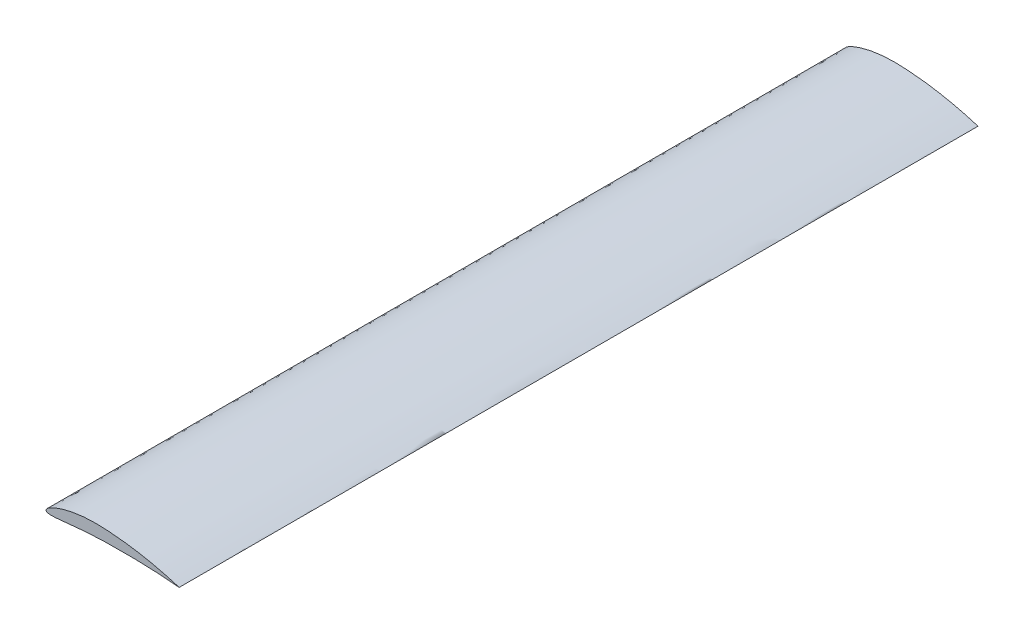
SolidWorks part; units mm, degrees
ref_plane "Front Plane" through (0, 0, 0) normal (0, 0, 1) x (1, 0, 0)
ref_plane "Top Plane" through (0, 0, 0) normal (0, 1, 0) x (1, 0, 0)
ref_plane "Right Plane" through (0, 0, 0) normal (1, 0, 0) x (0, 0, -1)
curve "Curve1"
  spline degree 3 poles (302.9843, 0.2066, 0) (305.2463, -0.0888, 0) (303.0423, 0.5058, 0) (301.2607, 1.1313, 0) (296.8595, 2.4314, 0) (291.4283, 4.0595, 0) (284.2715, 6.1062, 0) (275.7591, 8.441, 0) (265.8676, 11.0139, 0) (254.7283, 13.724, 0) (242.4522, 16.5013, 0) (229.1619, 19.2495, 0) (215.0022, 21.8919, 0) (200.1221, 24.3477, 0) (184.6818, 26.5449, 0) (168.8517, 28.4234, 0) (152.8082, 29.9307, 0) (136.7266, 31.0049, 0) (120.7051, 31.6889, 0) (104.9137, 31.6962, 0) (89.5649, 30.8862, 0) (74.9378, 29.3709, 0) (61.2207, 27.2233, 0) (48.5868, 24.554, 0) (37.1861, 21.5011, 0) (27.1553, 18.1971, 0) (18.5969, 14.8045, 0) (11.6064, 11.436, 0) (6.2054, 8.2632, 0) (2.4621, 5.3102, 0) (0.1728, 2.7181, 0) (-0.3667, -0.1067, 0) (1.6185, -2.1752, 0) (4.9031, -3.1118, 0) (9.5405, -3.659, 0) (15.6223, -3.6847, 0) (23.0877, -3.3095, 0) (31.8617, -2.5607, 0) (41.8437, -1.5362, 0) (52.932, -0.3245, 0) (65.0085, 0.9827, 0) (77.9641, 2.2775, 0) (91.674, 3.4466, 0) (106.0204, 4.4121, 0) (120.9553, 5.0518, 0) (136.3391, 5.4103, 0) (152.0077, 5.7293, 0) (167.7158, 5.8914, 0) (183.2867, 5.9078, 0) (198.553, 5.7595, 0) (213.3478, 5.4574, 0) (227.5084, 5.0134, 0) (240.8771, 4.4585, 0) (253.3023, 3.8196, 0) (264.6365, 3.1406, 0) (274.7593, 2.4517, 0) (283.5118, 1.8033, 0) (290.9024, 1.2074, 0) (296.5367, 0.7424, 0) (301.0977, 0.3102, 0) (302.9843, 0.2066, 0) (305.2463, -0.0888, 0) (303.0423, 0.5058, 0) knots -0.012269 -0.005489 -0.001366 0 0.001375 0.005484 0.012273 0.021682 0.033581 0.047831 0.064306 0.082777 0.103064 0.124929 0.148149 0.172445 0.197572 0.223269 0.249228 0.275186 0.300901 0.326463 0.351222 0.374906 0.39727 0.418072 0.43708 0.454093 0.46892 0.481392 0.491447 0.499024 0.504294 0.507922 0.51154 0.516781 0.524216 0.533992 0.546034 0.56022 0.576403 0.594371 0.613951 0.634917 0.657089 0.68023 0.704175 0.72909 0.754354 0.779668 0.80476 0.829359 0.853209 0.876041 0.897604 0.917662 0.93597 0.95231 0.966503 0.97835 0.987731 0.994511 0.998634 1 1.001375 1.005484 1.012273 periodic
sketch "Sketch1" plane through (0, 0, 0) normal (0, 0, 1) x (1, 0, 0)
  spline S1 degree 3 poles (303.4383, 0.1549) (305.1347, -0.0666) (303.4817, 0.3793) (302.1455, 0.8485) (298.8446, 1.8235) (294.7713, 3.0446) (289.4036, 4.5797) (283.0193, 6.3308) (275.6007, 8.2604) (267.2462, 10.293) (258.0391, 12.376) (248.0714, 14.4371) (237.4517, 16.4189) (226.2916, 18.2607) (214.7114, 19.9087) (202.8388, 21.3175) (190.8061, 22.448) (178.7449, 23.2537) (166.7288, 23.7667) (154.8853, 23.7721) (143.3737, 23.1647) (132.4034, 22.0282) (122.1155, 20.4175) (112.6401, 18.4155) (104.0896, 16.1258) (96.5665, 13.6478) (90.1477, 11.1034) (84.9048, 8.577) (80.854, 6.1974) (78.0466, 3.9827) (76.3296, 2.0386) (75.925, -0.08) (77.4139, -1.6314) (79.8773, -2.3338) (83.3554, -2.7443) (87.9167, -2.7635) (93.5158, -2.4821) (100.0963, -1.9205) (107.5828, -1.1521) (115.899, -0.2434) (124.9564, 0.7371) (134.6731, 1.7081) (144.9555, 2.585) (155.7153, 3.3091) (166.9165, 3.7888) (178.4544, 4.0577) (190.2058, 4.297) (201.9868, 4.4185) (213.6651, 4.4309) (225.1148, 4.3196) (236.2108, 4.093) (246.8313, 3.76) (256.8578, 3.3439) (266.1768, 2.8647) (274.6774, 2.3555) (282.2695, 1.8388) (288.8338, 1.3525) (294.3768, 0.9055) (298.6025, 0.5568) (302.0233, 0.2327) (303.4383, 0.1549) (305.1347, -0.0666) (303.4817, 0.3793) knots -0.012269 -0.005489 -0.001366 0 0.001375 0.005484 0.012273 0.021682 0.033581 0.047831 0.064306 0.082777 0.103064 0.124929 0.148149 0.172445 0.197572 0.223269 0.249228 0.275186 0.300901 0.326463 0.351222 0.374906 0.39727 0.418072 0.43708 0.454093 0.46892 0.481392 0.491447 0.499024 0.504294 0.507922 0.51154 0.516781 0.524216 0.533992 0.546034 0.56022 0.576403 0.594371 0.613951 0.634917 0.657089 0.68023 0.704175 0.72909 0.754354 0.779668 0.80476 0.829359 0.853209 0.876041 0.897604 0.917662 0.93597 0.95231 0.966503 0.97835 0.987731 0.994511 0.998634 1 1.001375 1.005484 1.012273 only from (304.8, 0) to (304.8, 0)
extrude "Boss-Extrude1" add sketch "Sketch1" along normal blind 1371.6
sketch "Sketch2" plane through (0, 0, 0) normal (0, 0, -1) x (-1, 0, 0)
  line L1 (-304.8, 0) -> (-76.2, 0) construction
  line L2 (-304.8, 0) -> (-304.8, -34.4887) construction
  line L3 (-76.2, 0) -> (-76.2, -19.8652) construction
  spline S0 degree 3 poles (-303.0423, 0.5058) (-305.2463, -0.0888) (-302.9843, 0.2066) (-301.0977, 0.3102) (-296.5367, 0.7424) (-290.9024, 1.2074) (-283.5118, 1.8033) (-274.7593, 2.4517) (-264.6365, 3.1406) (-253.3023, 3.8196) (-240.8771, 4.4585) (-227.5084, 5.0134) (-213.3478, 5.4574) (-198.553, 5.7595) (-183.2867, 5.9078) (-167.7158, 5.8914) (-152.0077, 5.7293) (-136.3391, 5.4103) (-120.9553, 5.0518) (-106.0204, 4.4121) (-91.674, 3.4466) (-77.9641, 2.2775) (-65.0085, 0.9827) (-52.932, -0.3245) (-41.8437, -1.5362) (-31.8617, -2.5607) (-23.0877, -3.3095) (-15.6223, -3.6847) (-9.5405, -3.659) (-4.9031, -3.1118) (-1.6185, -2.1752) (0.3667, -0.1067) (-0.1728, 2.7181) (-2.4621, 5.3102) (-6.2054, 8.2632) (-11.6064, 11.436) (-18.5969, 14.8045) (-27.1553, 18.1971) (-37.1861, 21.5011) (-48.5868, 24.554) (-61.2207, 27.2233) (-74.9378, 29.3709) (-89.5649, 30.8862) (-104.9137, 31.6962) (-120.7051, 31.6889) (-136.7266, 31.0049) (-152.8082, 29.9307) (-168.8517, 28.4234) (-184.6818, 26.5449) (-200.1221, 24.3477) (-215.0022, 21.8919) (-229.1619, 19.2495) (-242.4522, 16.5013) (-254.7283, 13.724) (-265.8676, 11.0139) (-275.7591, 8.441) (-284.2715, 6.1062) (-291.4283, 4.0595) (-296.8595, 2.4314) (-301.2607, 1.1313) (-303.0423, 0.5058) (-305.2463, -0.0888) (-302.9843, 0.2066) knots -0.012273 -0.005484 -0.001375 0 0.001366 0.005489 0.012269 0.02165 0.033497 0.04769 0.06403 0.082338 0.102396 0.123959 0.146791 0.170641 0.19524 0.220332 0.245646 0.27091 0.295825 0.31977 0.342911 0.365083 0.386049 0.405629 0.423597 0.43978 0.453966 0.466008 0.475784 0.483219 0.48846 0.492078 0.495706 0.500976 0.508553 0.518608 0.53108 0.545907 0.56292 0.581928 0.60273 0.625094 0.648778 0.673537 0.699099 0.724814 0.750772 0.776731 0.802428 0.827555 0.851851 0.875071 0.896936 0.917223 0.935694 0.952169 0.966419 0.978318 0.987727 0.994516 0.998625 1 1.001366 1.005489 1.012269 only from (-304.8, 0) to (-304.8, 0) construction
  spline S1 degree 3 poles (-303.4817, 0.3793) (-305.1347, -0.0666) (-303.4383, 0.1549) (-302.0233, 0.2327) (-298.6025, 0.5568) (-294.3768, 0.9055) (-288.8338, 1.3525) (-282.2695, 1.8388) (-274.6774, 2.3555) (-266.1768, 2.8647) (-256.8578, 3.3439) (-246.8313, 3.76) (-236.2108, 4.093) (-225.1148, 4.3196) (-213.6651, 4.4309) (-201.9868, 4.4185) (-190.2058, 4.297) (-178.4544, 4.0577) (-166.9165, 3.7888) (-155.7153, 3.3091) (-144.9555, 2.585) (-134.6731, 1.7081) (-124.9564, 0.7371) (-115.899, -0.2434) (-107.5828, -1.1521) (-100.0963, -1.9205) (-93.5158, -2.4821) (-87.9167, -2.7635) (-83.3554, -2.7443) (-79.8773, -2.3338) (-77.4139, -1.6314) (-75.925, -0.08) (-76.3296, 2.0386) (-78.0466, 3.9827) (-80.854, 6.1974) (-84.9048, 8.577) (-90.1477, 11.1034) (-96.5665, 13.6478) (-104.0896, 16.1258) (-112.6401, 18.4155) (-122.1155, 20.4175) (-132.4034, 22.0282) (-143.3737, 23.1647) (-154.8853, 23.7721) (-166.7288, 23.7667) (-178.7449, 23.2537) (-190.8061, 22.448) (-202.8388, 21.3175) (-214.7114, 19.9087) (-226.2916, 18.2607) (-237.4517, 16.4189) (-248.0714, 14.4371) (-258.0391, 12.376) (-267.2462, 10.293) (-275.6007, 8.2604) (-283.0193, 6.3308) (-289.4036, 4.5797) (-294.7713, 3.0446) (-298.8446, 1.8235) (-302.1455, 0.8485) (-303.4817, 0.3793) (-305.1347, -0.0666) (-303.4383, 0.1549) knots -0.012273 -0.005484 -0.001375 0 0.001366 0.005489 0.012269 0.02165 0.033497 0.04769 0.06403 0.082338 0.102396 0.123959 0.146791 0.170641 0.19524 0.220332 0.245646 0.27091 0.295825 0.31977 0.342911 0.365083 0.386049 0.405629 0.423597 0.43978 0.453966 0.466008 0.475784 0.483219 0.48846 0.492078 0.495706 0.500976 0.508553 0.518608 0.53108 0.545907 0.56292 0.581928 0.60273 0.625094 0.648778 0.673537 0.699099 0.724814 0.750772 0.776731 0.802428 0.827555 0.851851 0.875071 0.896936 0.917223 0.935694 0.952169 0.966419 0.978318 0.987727 0.994516 0.998625 1 1.001366 1.005489 1.012269 only from (-304.8, 0) to (-304.8, 0) construction
ref_plane "Plane1" through (0, 0, 685.8) normal (0, 0, -1) x (-1, 0, 0)
sketch3d "3DSketch1"
  line L0 (304.8, 0, 0) -> (304.8, 0, -1.7227) construction
